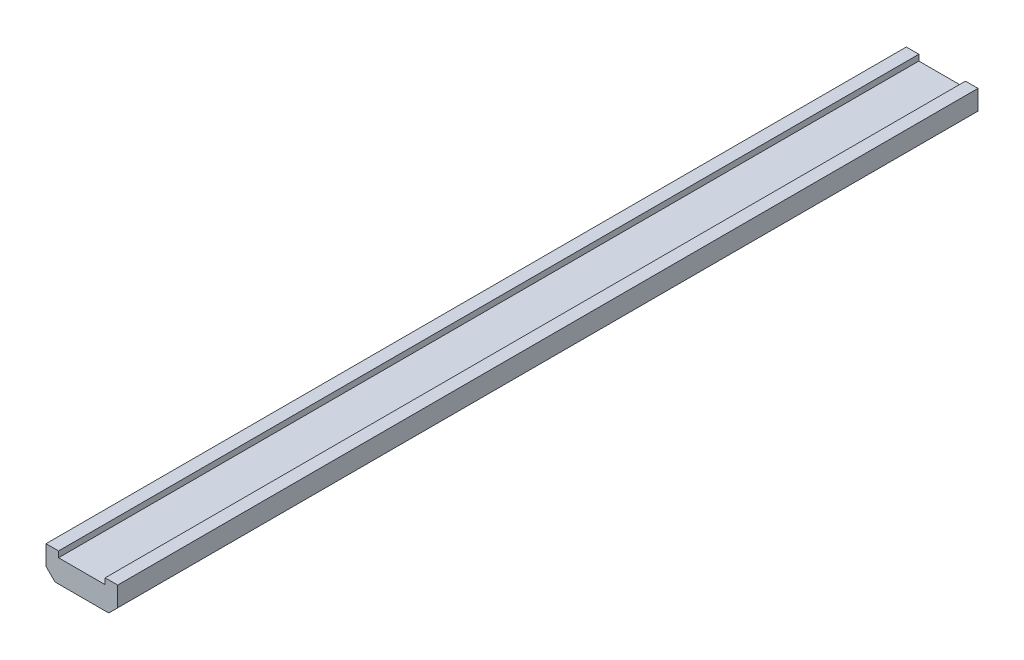
SolidWorks part; units mm, degrees
ref_plane "Front Plane" through (0, 0, 0) normal (0, 0, 1) x (1, 0, 0)
ref_plane "Top Plane" through (0, 0, 0) normal (0, 1, 0) x (1, 0, 0)
ref_plane "Right Plane" through (0, 0, 0) normal (1, 0, 0) x (0, 0, -1)
sketch "Sketch1" plane through (0, 0, 0) normal (0, 1, 0) x (1, 0, 0)
  line L1 (-100, 1200) -> (100, 1200)
  line L2 (-100, 1200) -> (-100, -1200)
  line L3 (-100, -1200) -> (100, -1200)
  line L4 (100, 1200) -> (100, -1200)
  line L5 (-100, 1200) -> (100, -1200) construction
  line L6 (-100, -1200) -> (100, 1200) construction
  point P0 (0, 0)
extrude "Boss-Extrude1" add sketch "Sketch1" along normal blind 80
chamfer "Chamfer1" distance 25 angle 45 2 edges at (-100, 0, 0) (100, 0, 0)
sketch "Sketch2" plane through (0, 80, 0) normal (0, 1, 0) x (1, 0, 0)
  line L0 (-100, -1200) -> (100, -1200) construction
  line L1 (-65, 1200) -> (65, 1200)
  line L2 (-65, 1200) -> (-65, -1200)
  line L3 (-65, -1200) -> (65, -1200)
  line L4 (65, 1200) -> (65, -1200)
  line L5 (-65, 1200) -> (65, -1200) construction
  line L6 (-65, -1200) -> (65, 1200) construction
  point P0 (0, 0)
extrude "Cut-Extrude1" cut sketch "Sketch2" against normal blind 16.5174
